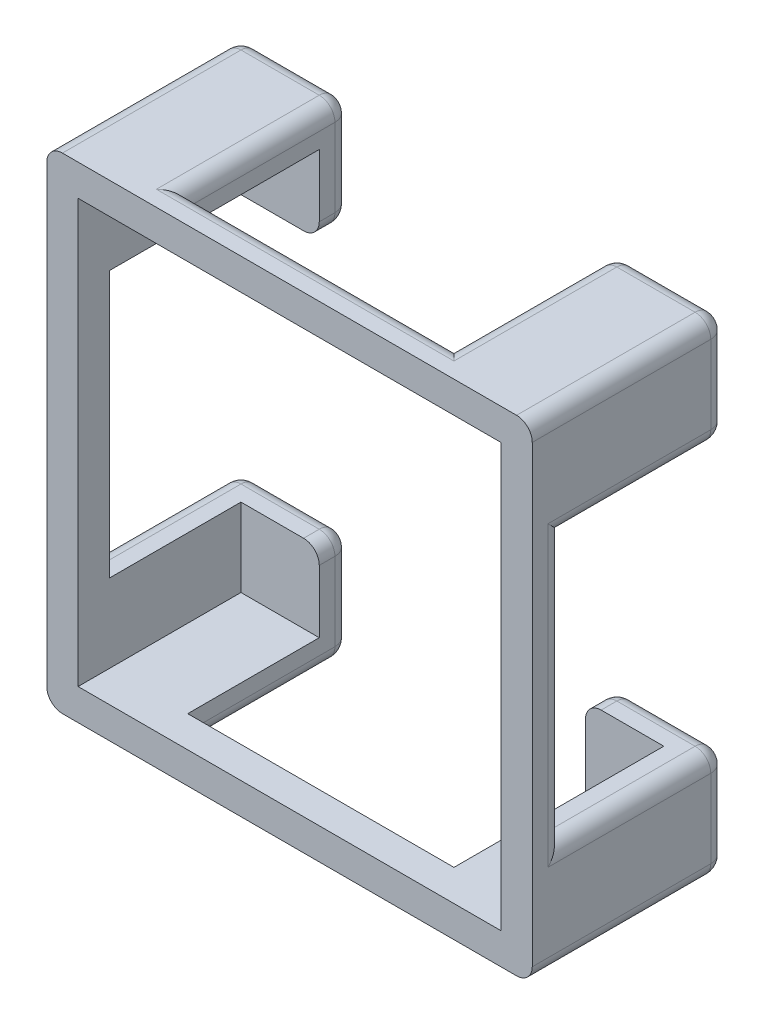
SolidWorks part; units mm, degrees
ref_plane "Front Plane" through (0, 0, 0) normal (0, 0, 1) x (1, 0, 0)
ref_plane "Top Plane" through (0, 0, 0) normal (0, 1, 0) x (1, 0, 0)
ref_plane "Right Plane" through (0, 0, 0) normal (1, 0, 0) x (0, 0, -1)
sketch "Sketch1" plane through (0, 0, 0) normal (0, 0, 1) x (1, 0, 0)
  line L0 (0, 0) -> (0, -2) construction
  line L1 (0, 0) -> (27, 0)
  line L2 (0, 0) -> (0, 27)
  line L3 (0, 27) -> (27, 27)
  line L4 (27, 0) -> (27, 27)
  line L5 (-2, -2) -> (29, -2)
  line L6 (-2, -2) -> (-2, 29)
  line L7 (-2, 29) -> (29, 29)
  line L8 (29, -2) -> (29, 29)
  line L9 (27, 27) -> (29, 27) construction
  line L10 (-2, 0) -> (0, 0) construction
  line L11 (27, 29) -> (27, 27) construction
  dimension "D1" = 27
  dimension "D2" = 27
  dimension "D3" = 2
extrude "Boss-Extrude1" add sketch "Sketch1" along normal blind 2
sketch "Sketch2" plane through (0, 0, 0) normal (0, 0, -1) x (-1, 0, 0)
  line L0 (-29, 29) -> (-22, 29)
  line L1 (-29, 29) -> (2, 29) construction
  line L2 (-22, 29) -> (-22, 27)
  line L3 (-27, 27) -> (0, 27) construction
  line L4 (-22, 27) -> (-27, 27)
  line L5 (-27, 27) -> (-27, 22)
  line L6 (-27, 0) -> (-27, 27) construction
  line L7 (-27, 22) -> (-29, 22)
  line L8 (-29, -2) -> (-29, 29) construction
  line L9 (-29, 22) -> (-29, 29)
  line L10 (2, 29) -> (-5, 29)
  line L11 (-5, 29) -> (-5, 27)
  line L12 (-5, 27) -> (0, 27)
  line L13 (0, 27) -> (0, 22)
  line L14 (0, 27) -> (0, 0) construction
  line L15 (0, 22) -> (2, 22)
  line L16 (2, 29) -> (2, -2) construction
  line L17 (2, 22) -> (2, 29)
  line L18 (2, 5) -> (2, -2)
  line L19 (2, -2) -> (-5, -2)
  line L20 (2, -2) -> (-29, -2) construction
  line L21 (-5, -2) -> (-5, 0)
  line L22 (0, 0) -> (-27, 0) construction
  line L23 (-5, 0) -> (0, 0)
  line L24 (0, 0) -> (0, 5)
  line L25 (0, 5) -> (2, 5)
  line L26 (-29, -2) -> (-29, 5)
  line L27 (-29, 5) -> (-27, 5)
  line L28 (-27, 5) -> (-27, 0)
  line L29 (-27, 0) -> (-22, 0)
  line L30 (-22, 0) -> (-22, -2)
  line L31 (-22, -2) -> (-29, -2)
  dimension "D1" = 5
extrude "Boss-Extrude2" add sketch "Sketch2" along normal blind 8.4
sketch "Sketch4" plane through (0, 0, -8.4) normal (0, 0, -1) x (-1, 0, 0)
  line L0 (-22, 27) -> (-22, 29) construction
  line L1 (-29, 29) -> (-22, 29)
  line L2 (-29, 29) -> (-29, 22)
  line L3 (-29, 22) -> (-22, 22)
  line L4 (-22, 29) -> (-22, 22)
  line L5 (-29, -2) -> (-22, -2)
  line L6 (-29, -2) -> (-29, 5)
  line L7 (-29, 5) -> (-22, 5)
  line L8 (-22, -2) -> (-22, 5)
  line L9 (2, -2) -> (-5, -2)
  line L10 (2, -2) -> (2, 5)
  line L11 (2, 5) -> (-5, 5)
  line L12 (-5, -2) -> (-5, 5)
  line L13 (2, 29) -> (-5, 29)
  line L14 (2, 29) -> (2, 22)
  line L15 (2, 22) -> (-5, 22)
  line L16 (-5, 29) -> (-5, 22)
  line L17 (-29, 22) -> (-27, 22) construction
  line L18 (-27, 5) -> (-29, 5) construction
  line L19 (-22, -2) -> (-22, 0) construction
  line L20 (-5, 0) -> (-5, -2) construction
  line L21 (2, 5) -> (0, 5) construction
  line L22 (0, 22) -> (2, 22) construction
  line L23 (-5, 29) -> (-5, 27) construction
extrude "Boss-Extrude3" add sketch "Sketch4" along normal blind 2
fillet "Fillet1" radius 1 36 edges at (-2, 25.5, -10.4) (1.5, 29, -10.4) (-2, 29, -4.2) (-2, 22, -5.2) (5, 5, -9.4) (-2, 5, -5.2) (-2, 13.5, 0) (-2, -2, -4.2) (5, 1.5, -10.4) (1.5, 5, -10.4) (-2, 1.5, -10.4) (1.5, -2, -10.4) (5, -2, -5.2) (13.5, -2, 0) (22, 5, -9.4) (22, -2, -5.2) (29, -2, -4.2) (25.5, -2, -10.4) (22, 22, -9.4) (5, 22, -9.4) (22, 1.5, -10.4) (25.5, 5, -10.4) (29, 1.5, -10.4) (29, 5, -5.2) (29, 29, -4.2) (29, 25.5, -10.4) (25.5, 22, -10.4) (25.5, 29, -10.4) (22, 25.5, -10.4) (5, 29, -5.2) (1.5, 22, -10.4) (5, 25.5, -10.4)
ref_plane "Plane1" through (0, 13.5, 0) normal (0, -1, 0) x (-1, 0, 0)
